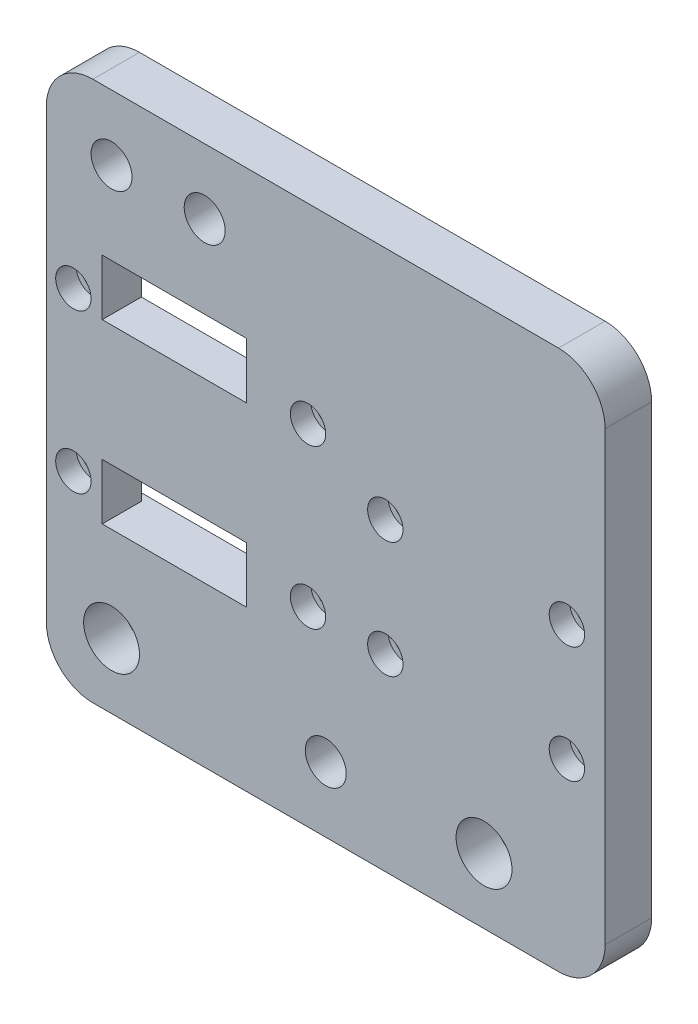
SolidWorks part; units mm, degrees
material "PEI"
ref_plane "前视基准面" through (0, 0, 0) normal (0, 0, 1) x (1, 0, 0)
ref_plane "上视基准面" through (0, 0, 0) normal (0, 1, 0) x (1, 0, 0)
ref_plane "右视基准面" through (0, 0, 0) normal (1, 0, 0) x (0, 0, -1)
other "Configuration Table"
sketch "草图1" plane through (0, 0, 0) normal (0, 0, 1) x (1, 0, 0)
  line L0 (27, 58) -> (27, 0) construction
  line L1 (0, 0) -> (54, 0)
  line L2 (0, 0) -> (0, 58)
  line L3 (0, 58) -> (54, 58)
  line L4 (54, 0) -> (54, 58)
  circle A0 centre (7, 7) radius 3
  circle A1 centre (47, 7) radius 3
  dimension "D3" = 6
  dimension "D1" = 54
  dimension "D2" = 58
  dimension "D4" = 20
  dimension "D5" = 7
extrude "凸台-拉伸1" add sketch "草图1" along normal blind 5
sketch "草图3" plane through (0, 0, 0) normal (0, 0, -1) x (-1, 0, 0)
  circle A0 centre (-47, 7) radius 6
  circle A1 centre (-7, 7) radius 6
  dimension "D1" = 12
  dimension "D2" = 12
extrude "切除-拉伸1" cut sketch "草图3" against normal blind 0.8
sketch "草图4" plane through (0, 0, 0) normal (0, 0, -1) x (-1, 0, 0)
  line L0 (-54, 29) -> (0, 29) construction
  line L1 (-54, 0) -> (-54, 58) construction
  line L2 (0, 58) -> (0, 0) construction
  circle A0 centre (-28.1, 37.5) radius 1.25
  circle A1 centre (-2.9, 37.5) radius 1.25
  circle A2 centre (-28.1, 20.5) radius 1.25
  circle A3 centre (-2.9, 20.5) radius 1.25
  dimension "D4" = 2.5
  dimension "D1" = 17
  dimension "D2" = 2.9
  dimension "D3" = 25.2
extrude "切除-拉伸2" cut sketch "草图4" against normal up to next
sketch "草图5" plane through (0, 0, 0) normal (0, 0, -1) x (-1, 0, 0)
  line L0 (-54, 29) -> (0, 29) construction
  line L1 (-54, 0) -> (-54, 58) construction
  line L2 (0, 58) -> (0, 0) construction
  line L4 (-31.5, 42.1403) -> (0, 42.1403)
  line L5 (-31.5, 42.1403) -> (-31.5, 17.1403)
  line L6 (-31.5, 17.1403) -> (0, 17.1403)
  line L7 (0, 42.1403) -> (0, 17.1403)
  dimension "D1" = 31.5
  dimension "D2" = 25
extrude "切除-拉伸3" cut sketch "草图5" against normal blind 0.8
sketch "草图6" plane through (0, 0, 0.8) normal (0, 0, -1) x (-1, 0, 0)
  line L0 (0, 17.1403) -> (0, 42.1403) construction
  line L1 (-21.5, 42.1403) -> (-6, 42.1403)
  line L2 (-21.5, 42.1403) -> (-21.5, 17.1403)
  line L3 (-21.5, 17.1403) -> (-6, 17.1403)
  line L4 (-6, 42.1403) -> (-6, 17.1403)
  line L5 (-31.5, 42.1403) -> (-31.5, 17.1403) construction
  line L6 (0, 42.1403) -> (-31.5, 42.1403) construction
  line L7 (-31.5, 17.1403) -> (0, 17.1403) construction
  line L9 (-21.5, 36.1403) -> (-6, 36.1403)
  line L10 (-21.5, 36.1403) -> (-21.5, 23.1403)
  line L11 (-21.5, 23.1403) -> (-6, 23.1403)
  line L12 (-6, 36.1403) -> (-6, 23.1403)
  line M8 (-31.5, 17.1403) -> (0, 17.1403)
  line M10 (0, 42.1403) -> (-31.5, 42.1403)
  dimension "D1" = 6
  dimension "D2" = 10
  dimension "D3" = 6
  dimension "D4" = 6
extrude "切除-拉伸4" cut sketch "草图6" against normal up to next contours L2 L9 L4 M10 | L11 L2 L4 M8
sketch "草图7" plane through (0, 0, 5) normal (0, 0, 1) x (1, 0, 0)
  circle A0 centre (2.9, 20.5) radius 1.25 construction
  circle A1 centre (28.1, 20.5) radius 1.25 construction
  circle A2 centre (28.1, 37.5) radius 1.25 construction
  circle A3 centre (2.9, 37.5) radius 1.25 construction
  circle A4 centre (2.9, 20.5) radius 1.25
  circle A5 centre (28.1, 20.5) radius 1.25
  circle A6 centre (28.1, 37.5) radius 1.25
  circle A7 centre (2.9, 37.5) radius 1.25
  circle A8 centre (2.9, 37.5) radius 1.9
  circle A9 centre (28.1, 37.5) radius 1.9
  circle A10 centre (28.1, 20.5) radius 1.9
  circle A11 centre (2.9, 20.5) radius 1.9
  dimension "D1" = 3.8
extrude "切除-拉伸5" cut sketch "草图7" against normal blind 2.2
sketch "草图8" plane through (54, 0, 0) normal (1, 0, 0) x (0, 0, -1)
  line L4 (0, 0) -> (0, 58)
  line L5 (0, 58) -> (-5, 58)
  line L6 (-5, 58) -> (-5, 0)
  line L7 (-5, 0) -> (0, 0)
  line L8 (0, 0) -> (0, 58)
  line L9 (0, 58) -> (-5, 58)
  line L10 (-5, 58) -> (-5, 0)
  line L11 (-5, 0) -> (0, 0)
  dimension "D1" = 0
extrude "凸台-拉伸2" add sketch "草图8" along normal blind 6
sketch "草图9" plane through (0, 0, 0) normal (0, 0, -1) x (-1, 0, 0)
  line L1 (-31.5, 17.1403) -> (-59, 17.1403)
  line L2 (-31.5, 17.1403) -> (-31.5, 50.6403)
  line L3 (-31.5, 50.6403) -> (-59, 50.6403)
  line L4 (-59, 17.1403) -> (-59, 50.6403)
  dimension "D1" = 27.5
  dimension "D2" = 33.5
extrude "切除-拉伸6" cut sketch "草图9" against normal up to surface (0.8 mm away) up to face at (14.4167, 29.6403, 0.8)
sketch "草图10" plane through (0, 0, 0.8) normal (0, 0, -1) x (-1, 0, 0)
  line L0 (-59, 17.1403) -> (-21.5, 17.1403) construction
  line L1 (-59, 17.1403) -> (-59, 50.6403) construction
  circle A0 centre (-36.4, 20.2403) radius 1.25
  circle A1 centre (-36.4, 32.7403) radius 1.25
  circle A2 centre (-55.9, 32.7403) radius 1.25
  circle A3 centre (-55.9, 20.2403) radius 1.25
  dimension "D1" = 2.5
  dimension "D2" = 3.1
  dimension "D3" = 3.1
  dimension "D4" = 12.5
  dimension "D5" = 19.5
extrude "切除-拉伸7" cut sketch "草图10" against normal up to surface (4.2 mm away) contours A2 | A3 | A0 | A1 up to face at (4.8, 20.5, 5)
sketch "草图11" plane through (0, 0, 5) normal (0, 0, 1) x (1, 0, 0)
  circle A0 centre (36.4, 20.2403) radius 1.9
  circle A1 centre (55.9, 20.2403) radius 1.9
  circle A2 centre (55.9, 32.7403) radius 1.9
  circle A3 centre (36.4, 32.7403) radius 1.9
  circle A4 centre (28.1, 20.5) radius 1.9 construction
extrude "切除-拉伸8" cut sketch "草图11" against normal up to surface (2.2 mm away) up to face at (4.15, 20.5, 2.8)
fillet "圆角1" radius 5 4 edges at (60, 58, 2.5) (0, 58, 2.5) (0, 0, 2.5) (60, 0, 2.5)
sketch "草图12" plane through (0, 0, 0) normal (0, 0, -1) x (-1, 0, 0)
  line L0 (-60, 5) -> (-60, 53) construction
  line L1 (-60, 13.1403) -> (0, 13.1403)
  line L2 (-60, 13.1403) -> (-60, 16.1403)
  line L3 (-60, 16.1403) -> (0, 16.1403)
  line L4 (0, 13.1403) -> (0, 16.1403)
  line L5 (0, 17.1403) -> (0, 5) construction
  line L6 (-59, 17.1403) -> (-21.5, 17.1403) construction
  line L7 (-60, 51.6403) -> (-30.5, 51.6403)
  line L8 (-30.5, 51.6403) -> (-30.5, 43.1403)
  line L9 (-30.5, 43.1403) -> (0, 43.1403)
  line L10 (0, 53) -> (0, 42.1403) construction
  line L11 (-31.5, 50.6403) -> (-59, 50.6403) construction
  line L12 (-31.5, 42.1403) -> (-31.5, 50.6403) construction
  line L13 (0, 42.1403) -> (-31.5, 42.1403) construction
  line L14 (-60, 54.6403) -> (-27.5, 54.6403)
  line L15 (-27.5, 54.6403) -> (-27.5, 46.1403)
  line L16 (-27.5, 46.1403) -> (0, 46.1403)
  line L17 (-60, 5) -> (-60, 53)
  line L18 (0, 46.1403) -> (0, 43.1403)
  arc A0 (-55, 58) -> (-60, 53) centre (-55, 53) ccw construction
  arc A1 (-55, 58) -> (-60, 53) centre (-55, 53) ccw
  arc M7 (-55, 58) -> (-60, 53) centre (-55, 53) ccw
  line M8 (-60, 53) -> (-60, 5)
  line M12 (0, 5) -> (0, 17.1403)
  line M18 (0, 42.1403) -> (0, 53)
  dimension "D1" = 1
  dimension "D2" = 3
  dimension "D3" = 1
  dimension "D4" = 1
  dimension "D5" = 1
  dimension "D6" = 3
extrude "凸台-拉伸3" add sketch "草图12" along normal blind 20 separate body contours L3 L1 M8 M12 | L16 L15 L14 L7 L8 L9 M7 M8 M18
sketch "草图13" plane through (0, 0, -20) normal (0, 0, -1) x (-1, 0, 0)
  line L0 (0, 16.1403) -> (-60, 16.1403) construction
  line L1 (-60, 16.1403) -> (-60, 13.1403) construction
  line L2 (-60, 13.1403) -> (0, 13.1403) construction
  line L3 (0, 13.1403) -> (0, 16.1403) construction
  line L4 (0, 46.1403) -> (-27.5, 46.1403) construction
  line L5 (-27.5, 46.1403) -> (-27.5, 54.6403) construction
  line L6 (-27.5, 54.6403) -> (-59.7233, 54.6403) construction
  line L7 (-60, 53) -> (-60, 51.6403) construction
  line L8 (-60, 51.6403) -> (-30.5, 51.6403) construction
  line L9 (-30.5, 51.6403) -> (-30.5, 43.1403) construction
  line L10 (-30.5, 43.1403) -> (0, 43.1403) construction
  line L11 (0, 43.1403) -> (0, 46.1403) construction
  line L12 (0, 16.1403) -> (-60, 16.1403)
  line L13 (-60, 16.1403) -> (-60, 13.1403)
  line L14 (-60, 13.1403) -> (0, 13.1403)
  line L15 (0, 13.1403) -> (0, 16.1403)
  line L16 (0, 46.1403) -> (-27.5, 46.1403)
  line L17 (-27.5, 46.1403) -> (-27.5, 54.6403)
  line L18 (-27.5, 54.6403) -> (-59.7233, 54.6403)
  line L19 (-60, 53) -> (-60, 51.6403)
  line L20 (-60, 51.6403) -> (-30.5, 51.6403)
  line L21 (-30.5, 51.6403) -> (-30.5, 43.1403)
  line L22 (-30.5, 43.1403) -> (0, 43.1403)
  line L23 (0, 43.1403) -> (0, 46.1403)
  line L24 (-60, 51.6403) -> (-60, 16.1403)
  line L25 (0, 43.1403) -> (0, 16.1403)
  arc A0 (-59.7233, 54.6403) -> (-60, 53) centre (-55, 53) ccw construction
  arc A1 (-59.7233, 54.6403) -> (-60, 53) centre (-55, 53) ccw
  line M1 (0, 46.1403) -> (-27.5, 46.1403)
  line M2 (-27.5, 46.1403) -> (-27.5, 54.6403)
  line M3 (-27.5, 54.6403) -> (-59.7233, 54.6403)
  arc M4 (-59.7233, 54.6403) -> (-60, 53) centre (-55, 53) ccw
  line M5 (-60, 53) -> (-60, 51.6403)
  line M6 (-60, 51.6403) -> (-30.5, 51.6403)
  line M7 (-30.5, 51.6403) -> (-30.5, 43.1403)
  line M8 (-30.5, 43.1403) -> (0, 43.1403)
  line M9 (0, 43.1403) -> (0, 46.1403)
extrude "凸台-拉伸4" add sketch "草图13" along normal blind 3 contours L25 L24 L12 M8 M7 M6 | M9 M1 M2 M3 M4 M5 M6 M7 M8 | L14 L15 L12 L13
sketch "草图14" plane through (0, 0, 0) normal (0, 0, -1) x (-1, 0, 0)
  line L0 (0, 17.1403) -> (0, 5) construction
  line L1 (-5, 0) -> (-55, 0) construction
  line L2 (0, 53) -> (0, 42.1403) construction
  line L3 (-55, 58) -> (-5, 58) construction
  circle A0 centre (-30, 7) radius 2.2
  circle A1 centre (-17, 51) radius 2.2
  circle A2 centre (-7, 51) radius 2.2
  dimension "D1" = 4.4
  dimension "D2" = 30
  dimension "D3" = 7
  dimension "D4" = 7
  dimension "D5" = 10
  dimension "D6" = 7
extrude "切除-拉伸9" cut sketch "草图14" against normal up to surface (5 mm away) up to face at (38.3, 32.7403, 5)
sketch "草图15" plane through (0, 0, 0) normal (0, 0, 1) x (1, 0, 0)
  line L0 (27.5, 46.1403) -> (0, 46.1403) construction
  line L1 (7, 55.1403) -> (17, 55.1403)
  line L2 (2.5, 50.6403) -> (2.5, 46.1403)
  line L3 (2.5, 46.1403) -> (21.5, 46.1403)
  line L4 (21.5, 50.6403) -> (21.5, 46.1403)
  line L5 (60, 13.1403) -> (0, 13.1403) construction
  line L7 (25.5, 7) -> (25.5, 13.1403)
  line L8 (25.5, 13.1403) -> (34.5, 13.1403)
  line L9 (34.5, 7) -> (34.5, 13.1403)
  circle A0 centre (30, 7) radius 2.2 construction
  circle A1 centre (17, 51) radius 2.2 construction
  circle A2 centre (7, 51) radius 2.2 construction
  circle A3 centre (30, 7) radius 2.2
  circle A4 centre (17, 51) radius 2.2
  circle A5 centre (7, 51) radius 2.2
  arc A6 (21.5, 50.6403) -> (17, 55.1403) centre (17, 50.6403) ccw
  arc A7 (7, 55.1403) -> (2.5, 50.6403) centre (7, 50.6403) ccw
  arc A8 (25.5, 7) -> (30, 2.5) centre (30, 7) ccw
  circle A9 centre (30, 7) radius 4.5
  point P19 (2.5, 55.1403)
  line M7 (27.5, 46.1403) -> (0, 46.1403)
  dimension "D4" = 4.5
  dimension "D8" = 4.5
  dimension "D1" = 9
  dimension "D2" = 4.5
  dimension "D3" = 4.5
  dimension "D5" = 4.5
  dimension "D7" = 9
extrude "凸台-拉伸5" add sketch "草图15" against normal blind 5 contours A9 A8 A3 | A9 L9 L8 L7 | L1 A7 L2 L4 A6 A4 A5 M7
sketch "草图16" plane through (0, 46.1403, 0) normal (0, 1, 0) x (1, 0, 0)
  line L0 (27.5, 23) -> (27.5, 0) construction
  line L1 (0, 23) -> (27.5, 23)
  line L2 (0, 23) -> (0, 13)
  line L3 (0, 13) -> (27.5, 13)
  line L4 (27.5, 23) -> (27.5, 13)
  dimension "D1" = 10
extrude "切除-拉伸10" cut sketch "草图16" against normal up to surface (33 mm away) up to face at (30, 13.1403, -7)
sketch "草图17" plane through (27.5, 0, 0) normal (-1, 0, 0) x (0, 0, 1)
  line L0 (-13, 43.1403) -> (-13, 16.1403)
  line L10 (-23, 54.6403) -> (-23, 13.1403)
  line L11 (-23, 13.1403) -> (-13, 13.1403)
  line L12 (-13, 13.1403) -> (-13, 16.1403)
  line L13 (-13, 16.1403) -> (-20, 16.1403)
  line L14 (-20, 16.1403) -> (-20, 43.1403)
  line L15 (-20, 43.1403) -> (-13, 43.1403)
  line L16 (-13, 43.1403) -> (-13, 46.1403)
  line L17 (-13, 46.1403) -> (0, 46.1403)
  line L18 (0, 46.1403) -> (0, 54.6403)
  line L19 (0, 54.6403) -> (-23, 54.6403)
  line L20 (-23, 54.6403) -> (-23, 13.1403)
  line L21 (-23, 13.1403) -> (-13, 13.1403)
  line L22 (-13, 13.1403) -> (-13, 16.1403)
  line L23 (-13, 16.1403) -> (-20, 16.1403)
  line L24 (-20, 16.1403) -> (-20, 43.1403)
  line L25 (-20, 43.1403) -> (-13, 43.1403)
  line L26 (-13, 43.1403) -> (-13, 46.1403)
  line L27 (-13, 46.1403) -> (0, 46.1403)
  line L28 (0, 46.1403) -> (0, 54.6403)
  line L29 (0, 54.6403) -> (-23, 54.6403)
  line M14 (-13, 16.1403) -> (-20, 16.1403)
  line M15 (-20, 16.1403) -> (-20, 43.1403)
  line M16 (-20, 43.1403) -> (-13, 43.1403)
  dimension "D1" = 0
extrude "凸台-拉伸6" add sketch "草图17" against normal up to surface (3 mm away) contours L0 M16 M15 M14 up to face at (30.5, 47.3903, -10)
sketch "草图18" plane through (0, 0, -13) normal (0, 0, -1) x (-1, 0, 0)
  line L0 (-21.5, 36.1403) -> (-21.5, 42.1403) construction
  line L6 (-21.5, 17.1403) -> (-21.5, 23.1403) construction
  line L7 (-21.5, 23.1403) -> (-6, 23.1403) construction
  line L8 (-6, 23.1403) -> (-6, 17.1403) construction
  line L10 (0, 17.1403) -> (0, 42.1403) construction
  line L12 (-6, 42.1403) -> (-6, 36.1403) construction
  line L13 (-6, 36.1403) -> (-21.5, 36.1403) construction
  line L15 (-27.5, 16.1403) -> (-27.5, 13.1403) construction
  line L16 (-27.5, 13.1403) -> (0, 13.1403) construction
  line L17 (0, 13.1403) -> (0, 16.1403) construction
  line L18 (0, 43.1403) -> (0, 46.1403) construction
  line L19 (0, 46.1403) -> (-27.5, 46.1403) construction
  line L20 (-27.5, 46.1403) -> (-27.5, 43.1403) construction
  line L22 (-21.5, 36.1403) -> (-21.5, 42.1403)
  line L28 (-21.5, 17.1403) -> (-21.5, 23.1403)
  line L29 (-21.5, 23.1403) -> (-6, 23.1403)
  line L30 (-6, 23.1403) -> (-6, 17.1403)
  line L32 (0, 17.1403) -> (0, 42.1403)
  line L34 (-6, 42.1403) -> (-6, 36.1403)
  line L35 (-6, 36.1403) -> (-21.5, 36.1403)
  line L37 (-27.5, 16.1403) -> (-27.5, 13.1403)
  line L38 (-27.5, 13.1403) -> (0, 13.1403)
  line L39 (0, 13.1403) -> (0, 16.1403)
  line L40 (0, 43.1403) -> (0, 46.1403)
  line L41 (0, 46.1403) -> (-27.5, 46.1403)
  line L42 (-27.5, 46.1403) -> (-27.5, 43.1403)
  line L44 (-27.5, 46.1403) -> (-27.5, 13.1403)
  line L45 (0, 13.1403) -> (0, 46.1403)
  line L46 (-59, 17.1403) -> (0, 17.1403) construction
  line L47 (0, 42.1403) -> (-31.5, 42.1403) construction
  line L48 (-21.5, 17.1403) -> (-6, 17.1403)
  line L49 (-6, 42.1403) -> (-21.5, 42.1403)
  line M2 (0, 16.1403) -> (-27.5, 16.1403)
  line M3 (-27.5, 16.1403) -> (-27.5, 13.1403)
  line M4 (-27.5, 13.1403) -> (0, 13.1403)
  line M5 (0, 13.1403) -> (0, 16.1403)
extrude "凸台-拉伸8" add sketch "草图18" along normal blind 3 contours M5 M2 M3 M4 | L45 L32 L40 L41 L42 L44 L49 L34 L35 L22 L48 L28 L29 L30 M2
sketch "草图19" plane through (0, 54.6403, 0) normal (0, 1, 0) x (1, 0, 0)
  line L1 (43, 4.2) -> (34, 4.2) construction
  line L2 (34, 11.7) -> (34, 4.2) construction
  line L5 (43, 11.7) -> (43, 4.2) construction
  line L6 (49.05, 4.2) -> (54.85, 4.2) construction
  line L7 (54.85, 7.3) -> (49.05, 7.3) construction
  line L9 (43, 4.2) -> (34, 4.2)
  line L10 (34, 11.7) -> (34, 4.2)
  line L13 (43, 11.7) -> (43, 4.2)
  line L14 (49.05, 4.2) -> (54.85, 4.2)
  line L15 (54.85, 7.3) -> (49.05, 7.3)
  line L16 (54.85, 9.8) -> (49.05, 9.8)
  line L17 (49.05, 1.7) -> (54.85, 1.7)
  line L20 (34, 11.7) -> (34, 16.7)
  line L21 (34, 16.7) -> (43, 16.7)
  line L22 (43, 11.7) -> (43, 16.7)
  arc A0 (54.85, 4.2) -> (54.85, 7.3) centre (54.85, 5.75) ccw construction
  arc A1 (49.05, 7.3) -> (49.05, 4.2) centre (49.05, 5.75) ccw construction
  arc A2 (54.85, 4.2) -> (54.85, 7.3) centre (54.85, 5.75) ccw
  arc A3 (49.05, 7.3) -> (49.05, 4.2) centre (49.05, 5.75) ccw
  arc A4 (49.05, 9.8) -> (49.05, 1.7) centre (49.05, 5.75) ccw
  arc A5 (54.85, 1.7) -> (54.85, 9.8) centre (54.85, 5.75) ccw
  dimension "D2" = 5
  dimension "D1" = 2.5
extrude "切除-拉伸11" cut sketch "草图19" against normal up to surface (3 mm away)
sketch "草图20" plane through (0, 0, -23) normal (0, 0, -1) x (-1, 0, 0)
  line L0 (-50.5, 17.1403) -> (-40.5, 17.1403) construction
  line L1 (-50.5, 26.1403) -> (-50.5, 17.1403) construction
  line L2 (-40.5, 27.1403) -> (-49.5, 27.1403) construction
  line L3 (-49.5, 27.1403) -> (-50.5, 26.1403) construction
  line L4 (-40.5, 17.1403) -> (-40.5, 27.1403) construction
  line L5 (-58.5, 39.1403) -> (-58.5, 41.5403) construction
  line L6 (-58.5, 41.5403) -> (-50.8, 41.5403) construction
  line L7 (-50.5, 17.1403) -> (-40.5, 17.1403)
  line L8 (-50.5, 26.1403) -> (-50.5, 17.1403)
  line L9 (-40.5, 27.1403) -> (-49.5, 27.1403)
  line L10 (-49.5, 27.1403) -> (-50.5, 26.1403)
  line L11 (-40.5, 17.1403) -> (-40.5, 27.1403)
  line L12 (-58.5, 39.1403) -> (-58.5, 41.5403)
  line L13 (-58.5, 41.5403) -> (-50.8, 41.5403)
  line L14 (-41.5, 21.1403) -> (-48.5, 21.1403) construction
  line L15 (-58.5, 41.5403) -> (-50.8, 41.5403)
  line L16 (-58.5, 41.5403) -> (-58.5, 39.1403)
  line L17 (-58.5, 39.1403) -> (-50.8, 39.1403)
  line L18 (-50.8, 41.5403) -> (-50.8, 39.1403)
  line L19 (-49.5, 23.1403) -> (-41.5, 23.1403) construction
  line L20 (-41.5, 21.1403) -> (-48.5, 21.1403)
  line L21 (-49.5, 23.1403) -> (-41.5, 23.1403)
  line L22 (-58.5, 42.5403) -> (-50.8, 42.5403)
  line L23 (-49.8, 41.5403) -> (-49.8, 38.1403)
  line L24 (-58.5, 38.1403) -> (-49.8, 38.1403)
  line L25 (-59.5, 39.1403) -> (-59.5, 41.5403)
  line L26 (-60, 53) -> (-60, 13.1403) construction
  line L27 (-49.8, 38.1403) -> (-60, 38.1403)
  line L28 (-49.8, 38.1403) -> (-49.8, 42.5403)
  line L29 (-49.8, 42.5403) -> (-60, 42.5403)
  line L30 (-60, 38.1403) -> (-60, 42.5403)
  line L31 (-41.9025, 22.6403) -> (-40.5, 22.6403)
  line L32 (-48.5, 22.6403) -> (-41.9025, 22.6403)
  line L33 (-48.5, 22.6403) -> (-48.5, 21.6403)
  line L34 (-48.5, 21.6403) -> (-41.9025, 21.6403)
  line L35 (-41.9025, 22.6403) -> (-41.9025, 21.6403)
  line L36 (-40.5, 22.6403) -> (-50.5, 22.6403)
  line L37 (-41.9025, 21.6403) -> (-40.5, 21.6403)
  line L38 (-40.5, 21.6403) -> (-50.5, 21.6403)
  dimension "D2" = 0.5
  dimension "D3" = 0.5
  dimension "D1" = 1
extrude "切除-拉伸12" cut sketch "草图20" against normal up to surface (3 mm away)
ref_plane "基准面1" through (0, 29.6403, 0) normal (0, -1, 0) x (-1, 0, 0)
sketch "草图21" plane through (0, 0, 0) normal (-1, 0, 0) x (0, 0, 1)
  line L0 (5, 53) -> (5, 5) construction
  line L1 (-16, 13.1403) -> (-12, 13.1403)
  line L2 (-16, 13.1403) -> (-16, -4.8597)
  line L3 (-16, -4.8597) -> (-12, -4.8597)
  line L4 (-12, 13.1403) -> (-12, -4.8597)
  line L5 (-12, -4.8597) -> (5, -4.8597)
  line L6 (-12, -4.8597) -> (-12, -0.8597)
  line L7 (-12, -0.8597) -> (5, -0.8597)
  line L8 (5, -4.8597) -> (5, -0.8597)
  line M6 (-16, 13.1403) -> (0, 13.1403)
  dimension "D1" = 4
  dimension "D2" = 4
  dimension "D3" = 18
extrude "凸台-拉伸9" add sketch "草图21" against normal blind 20 contours L5 L8 L7 L4 | L4 L2 L3 M6
fillet "圆角2" radius 5 1 edges at (10, -4.8597, -16)
other "保存实体1"
delete or keep bodies "实体-删除/保留 1" type delete bodies bodies 127
